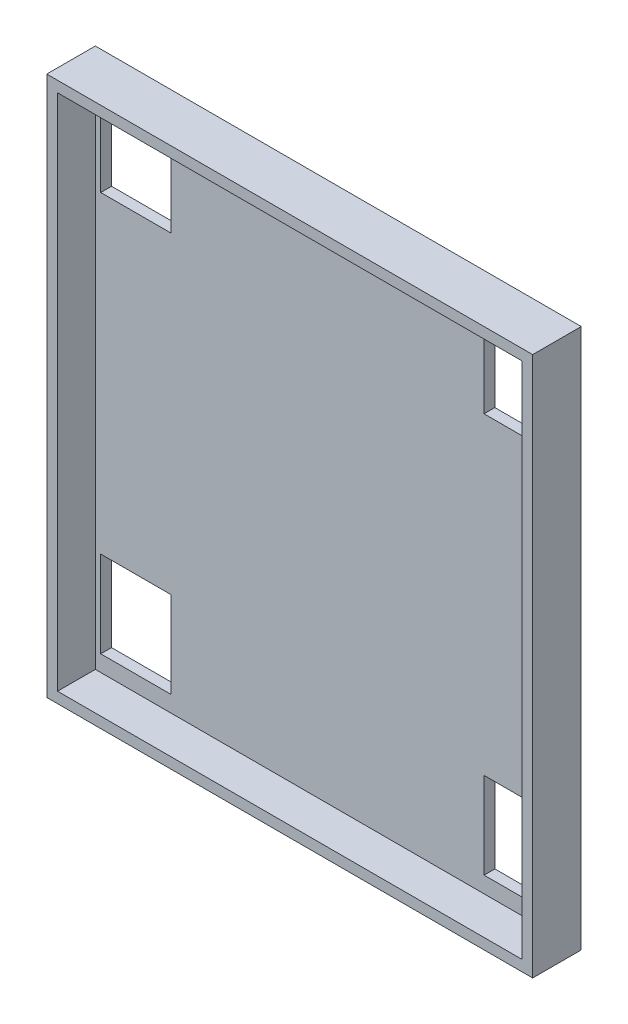
SolidWorks part; units mm, degrees
ref_plane "Plano frontal" through (0, 0, 0) normal (0, 0, 1) x (1, 0, 0)
ref_plane "Plano superior" through (0, 0, 0) normal (0, 1, 0) x (1, 0, 0)
ref_plane "Plano direito" through (0, 0, 0) normal (1, 0, 0) x (0, 0, -1)
sketch "Esboço1" plane through (0, 0, 0) normal (0, 0, 1) x (1, 0, 0)
  line L0 (-13.15, 0) -> (0, 0) construction
  line L1 (-45, 50) -> (45, 50)
  line L2 (-45, 50) -> (-45, -50)
  line L3 (-45, -50) -> (45, -50)
  line L4 (45, 50) -> (45, -50)
  line L5 (-45, 50) -> (45, -50) construction
  line L6 (-45, -50) -> (45, 50) construction
  line L7 (29, 45) -> (42, 45)
  line L8 (29, 45) -> (29, 29)
  line L9 (29, 29) -> (42, 29)
  line L10 (42, 45) -> (42, 29)
  line L11 (29, 45) -> (42, 29) construction
  line L12 (29, 29) -> (42, 45) construction
  line L13 (0, 20.1658) -> (0, 0) construction
  line L14 (29, -29) -> (42, -45) construction
  line L15 (29, -45) -> (42, -29) construction
  line L16 (42, -45) -> (42, -29)
  line L17 (29, -29) -> (42, -29)
  line L18 (29, -45) -> (29, -29)
  line L19 (29, -45) -> (42, -45)
  line L20 (-29, -45) -> (-42, -29) construction
  line L21 (-29, -29) -> (-42, -45) construction
  line L22 (-29, 29) -> (-42, 45) construction
  line L23 (-29, 45) -> (-42, 29) construction
  line L24 (-29, -45) -> (-42, -45)
  line L25 (-29, -45) -> (-29, -29)
  line L26 (-29, -29) -> (-42, -29)
  line L27 (-42, -45) -> (-42, -29)
  line L28 (-42, 45) -> (-42, 29)
  line L29 (-29, 29) -> (-42, 29)
  line L30 (-29, 45) -> (-29, 29)
  line L31 (-29, 45) -> (-42, 45)
  point P0 (0, 0)
  point P6 (35.5, 37)
  point P18 (35.5, -37)
  point P27 (-35.5, -37)
  point P28 (-35.5, 37)
  dimension "D1" = 100
  dimension "D2" = 90
  dimension "D3" = 3
  dimension "D4" = 5
  dimension "D5" = 16
  dimension "D6" = 13
extrude "Ressalto-extrusão1" add sketch "Esboço1" along normal blind 2
sketch "Esboço2" plane through (0, 0, 2) normal (0, 0, 1) x (1, 0, 0)
  line L0 (-43, -48) -> (43, -48)
  line L1 (-45, -50) -> (45, -50)
  line L2 (-45, -50) -> (-45, 50)
  line L3 (-45, 50) -> (45, 50)
  line L4 (45, -50) -> (45, 50)
  line L5 (-45, -50) -> (45, 50) construction
  line L6 (-45, 50) -> (45, -50) construction
  line L7 (43, -48) -> (43, 48)
  line L8 (-43, 48) -> (43, 48)
  line L9 (-43, -48) -> (-43, 48)
  point P0 (0, 0)
  dimension "D1" = 2
extrude "Ressalto-extrusão2" add sketch "Esboço2" along normal blind 7
